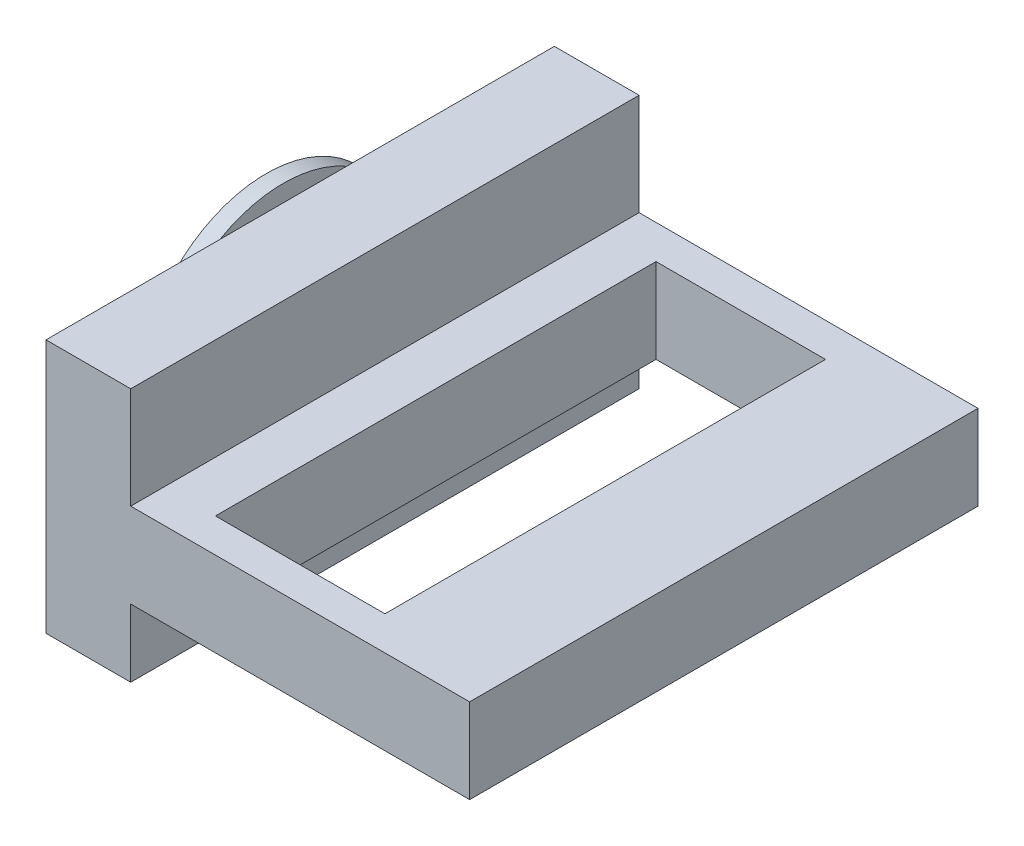
SolidWorks part; units mm, degrees
ref_plane "Front Plane" through (0, 0, 0) normal (0, 0, 1) x (1, 0, 0)
ref_plane "Top Plane" through (0, 0, 0) normal (0, 1, 0) x (1, 0, 0)
ref_plane "Right Plane" through (0, 0, 0) normal (1, 0, 0) x (0, 0, -1)
sketch "Sketch1" plane through (0, 0, 0) normal (0, 0, 1) x (1, 0, 0)
  line L0 (-10.1799, 6.185) -> (-10.1799, -8.815)
  line L1 (-10.1799, -8.815) -> (-5.1799, -8.815)
  line L2 (-5.1799, -8.815) -> (-5.1799, -4.815)
  line L3 (-5.1799, -4.815) -> (14.8201, -4.815)
  line L4 (14.8201, -4.815) -> (14.8201, 0.185)
  line L5 (14.8201, 0.185) -> (-5.1799, 0.185)
  line L6 (-5.1799, 0.185) -> (-5.1799, 6.185)
  line L7 (-5.1799, 6.185) -> (-10.1799, 6.185)
  dimension "D1" = 20
  dimension "D2" = 4
  dimension "D3" = 6
  dimension "D4" = 15
  dimension "D5" = 5
  dimension "D6" = 5
  dimension "D7" = 5
extrude "Boss-Extrude1" add sketch "Sketch1" along normal blind 30
sketch "Sketch2" plane through (0, 0.185, 0) normal (0, 1, 0) x (1, 0, 0)
  line L0 (-2.1799, -2) -> (-2.1799, -28)
  line L1 (-2.1799, -28) -> (7.8201, -28)
  line L2 (7.8201, -28) -> (7.8201, -2)
  line L3 (7.8201, -2) -> (-2.1799, -2)
  line L4 (14.8201, -30) -> (-5.1799, -30) construction
  dimension "D1" = 10
  dimension "D2" = 7
  dimension "D3" = 26
  dimension "D4" = 2
extrude "Cut-Extrude1" cut sketch "Sketch2" against normal blind 5
sketch "Sketch3" plane through (-10.1799, 0, 0) normal (-1, 0, 0) x (0, 0, 1)
  circle A0 centre (15, -1.315) radius 5
  dimension "D1" = 10
extrude "Boss-Extrude2" add sketch "Sketch3" along normal blind 1
sketch "Sketch4" plane through (-11.1799, 0, 0) normal (-1, 0, 0) x (0, 0, 1)
  circle A0 centre (15, -1.315) radius 7.5
  dimension "D1" = 15
extrude "Boss-Extrude3" add sketch "Sketch4" along normal blind 1
sketch "Sketch5" plane through (-12.1799, 0, 0) normal (-1, 0, 0) x (0, 0, 1)
  circle A0 centre (15, -1.315) radius 5
  dimension "D1" = 10
extrude "Boss-Extrude4" add sketch "Sketch5" along normal blind 1
